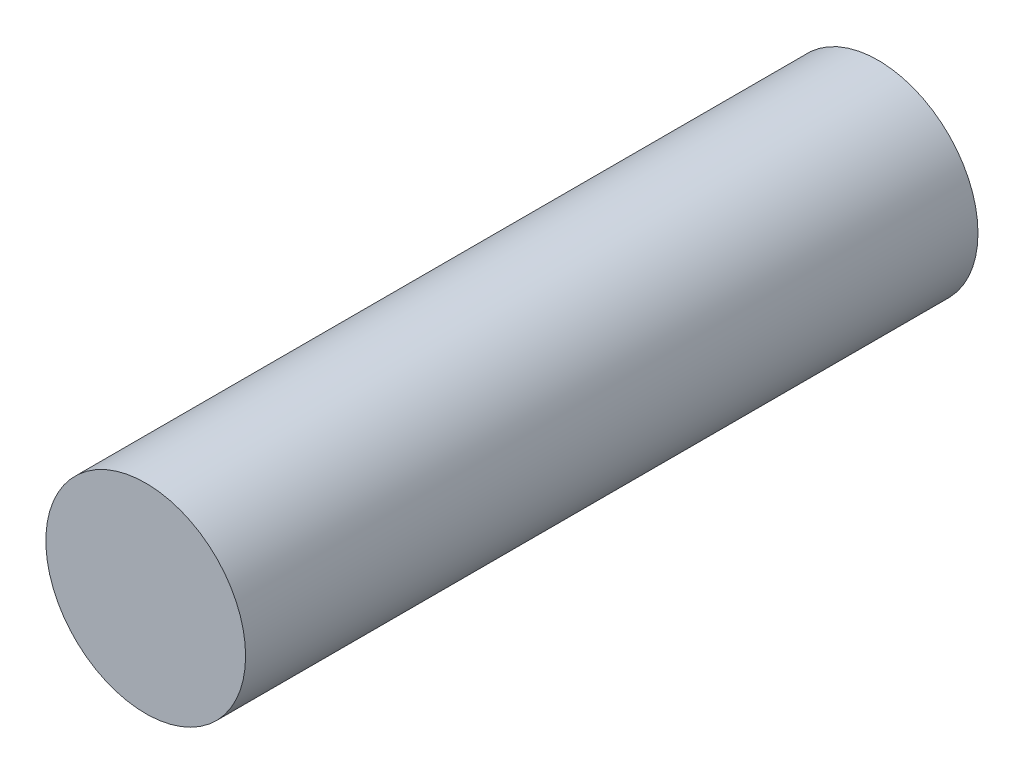
SolidWorks part; units mm, degrees
ref_plane "Alzado" through (0, 0, 0) normal (0, 0, 1) x (1, 0, 0)
ref_plane "Planta" through (0, 0, 0) normal (0, 1, 0) x (1, 0, 0)
ref_plane "Vista lateral" through (0, 0, 0) normal (1, 0, 0) x (0, 0, -1)
sketch "Croquis1" plane through (0, 0, 0) normal (0, 0, 1) x (1, 0, 0)
  circle A0 centre (0, 0) radius 9
  dimension "D1" = 18
extrude "Saliente-Extruir1" add sketch "Croquis1" along normal blind 66
